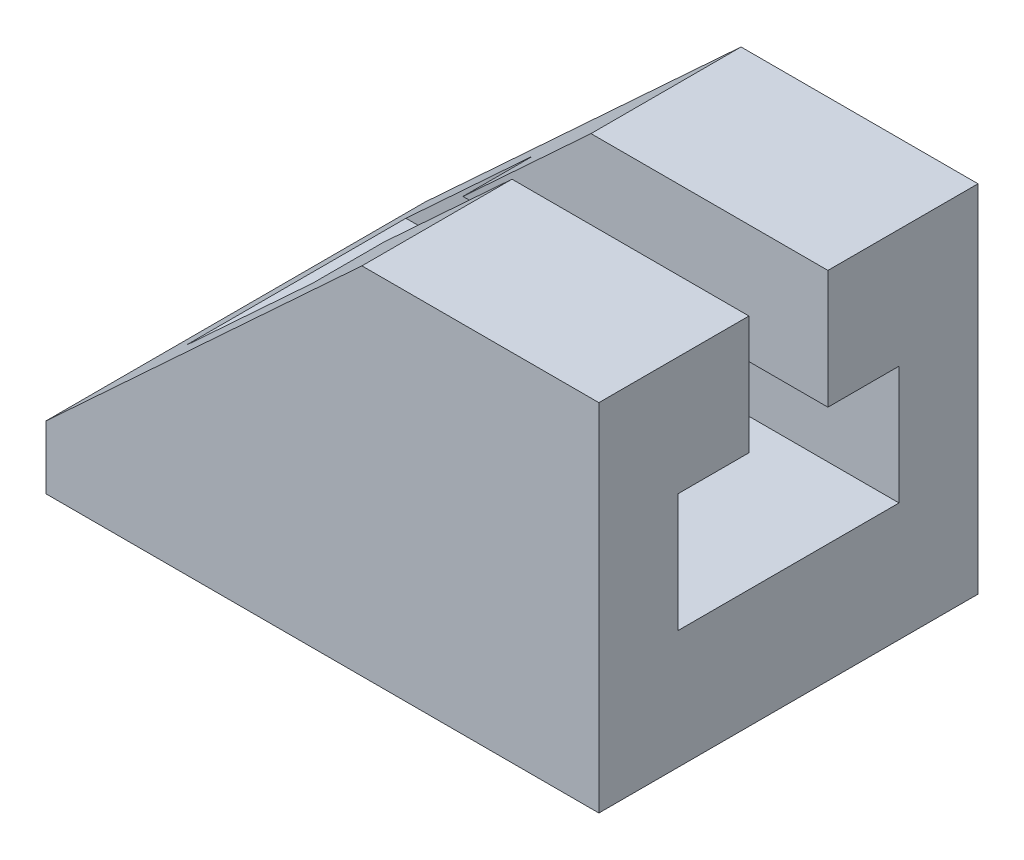
SolidWorks part; units mm, degrees
ref_plane "Front Plane" through (0, 0, 0) normal (0, 0, 1) x (1, 0, 0)
ref_plane "Top Plane" through (0, 0, 0) normal (0, 1, 0) x (1, 0, 0)
ref_plane "Right Plane" through (0, 0, 0) normal (1, 0, 0) x (0, 0, -1)
sketch "Sketch1" plane through (0, 0, 0) normal (0, 0, 1) x (1, 0, 0)
  line L0 (-73.6927, -34.6942) -> (-3.6927, -34.6942)
  line L1 (-3.6927, -34.6942) -> (-3.6927, 10.3058)
  line L2 (-3.6927, 10.3058) -> (-33.6927, 10.3058)
  line L3 (-73.6927, -34.6942) -> (-73.6927, -26.6942)
  line L4 (-73.6927, -26.6942) -> (-33.6927, 10.3058)
extrude "Boss-Extrude1" add sketch "Sketch1" along normal blind 48
sketch "Sketch2" plane through (-73.6927, 0, 0) normal (-1, 0, 0) x (0, 0, 1)
  line L0 (48, 10.3058) -> (0, 10.3058) construction
  line L1 (19, 10.3058) -> (29, 10.3058)
  line L2 (19, 10.3058) -> (19, -4.6942)
  line L4 (29, 10.3058) -> (29, -4.6942)
  line L5 (0, 10.3058) -> (0, -26.6942) construction
  line L6 (48, 10.3058) -> (48, -26.6942) construction
  line L7 (19, -4.6942) -> (10, -4.6942)
  line L8 (10, -4.6942) -> (10, -19.6942)
  line L9 (10, -19.6942) -> (38, -19.6942)
  line L10 (38, -19.6942) -> (38, -4.6942)
  line L11 (38, -4.6942) -> (29, -4.6942)
  dimension "D1" = 19
  dimension "D2" = 19
extrude "Cut-Extrude1" cut sketch "Sketch2" against normal blind 70
